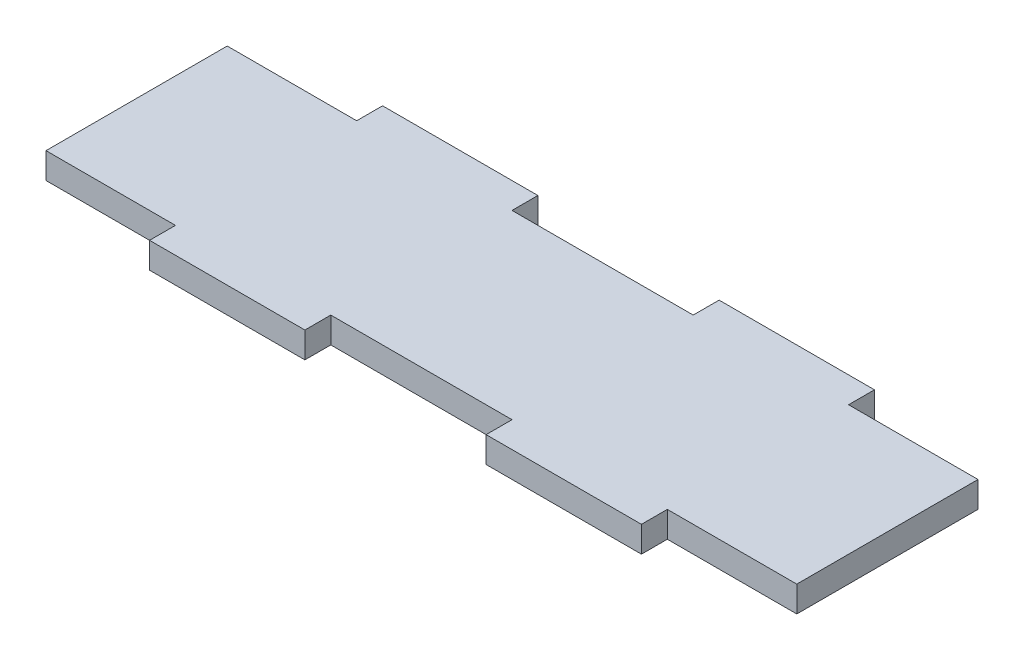
SolidWorks part; units mm, degrees
ref_plane "Plan de face" through (0, 0, 0) normal (0, 0, 1) x (1, 0, 0)
ref_plane "Plan de dessus" through (0, 0, 0) normal (0, 1, 0) x (1, 0, 0)
ref_plane "Plan de droite" through (0, 0, 0) normal (1, 0, 0) x (0, 0, -1)
sketch "Esquisse1" plane through (0, 0, 0) normal (0, 1, 0) x (1, 0, 0)
  line L0 (0, 0) -> (290, 0) construction
  line L1 (290, 0) -> (290, 10) construction
  line L2 (290, 10) -> (0, 10) construction
  line L3 (0, 10) -> (0, 0) construction
  line L4 (0, 10) -> (50, 10)
  line L5 (50, 10) -> (50, 0)
  line L6 (50, 0) -> (110, 0)
  line L7 (110, 0) -> (110, 10)
  line L8 (110, 10) -> (180, 10)
  line L9 (180, 10) -> (180, 0)
  line L10 (180, 0) -> (240, 0)
  line L11 (240, 0) -> (240, 10)
  line L12 (240, 10) -> (290, 10)
  line L13 (145, 10) -> (145, 0) construction
  line L14 (0, 10) -> (0, 80)
  line L15 (0, 45) -> (290, 45) construction
  line L16 (290, 80) -> (290, 10)
  line L17 (240, 80) -> (290, 80)
  line L18 (240, 90) -> (240, 80)
  line L19 (180, 90) -> (240, 90)
  line L20 (180, 80) -> (180, 90)
  line L21 (110, 80) -> (180, 80)
  line L22 (110, 90) -> (110, 80)
  line L23 (50, 90) -> (110, 90)
  line L24 (50, 80) -> (50, 90)
  line L25 (0, 80) -> (50, 80)
  dimension "D1" = 70
  dimension "D2" = 10
  dimension "D3" = 290
  dimension "D4" = 60
  dimension "D5" = 60
  dimension "D6" = 45
extrude "Boss.-Extru.1" add sketch "Esquisse1" along normal blind 10
